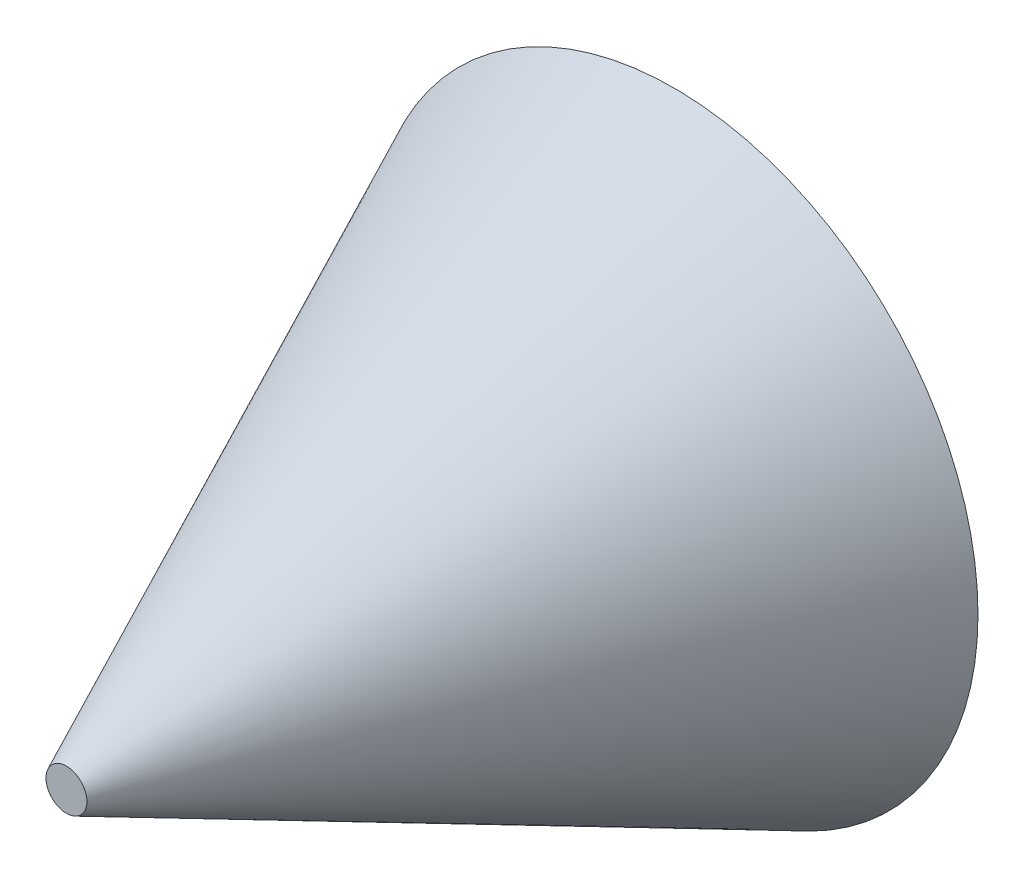
SolidWorks part; units mm, degrees
ref_plane "Front Plane" through (0, 0, 0) normal (0, 0, 1) x (1, 0, 0)
ref_plane "Top Plane" through (0, 0, 0) normal (0, 1, 0) x (1, 0, 0)
ref_plane "Right Plane" through (0, 0, 0) normal (1, 0, 0) x (0, 0, -1)
sketch "Sketch1" plane through (0, 0, 0) normal (0, 0, 1) x (1, 0, 0)
  circle A0 centre (0, 0) radius 12.5
  dimension "D1" = 25
extrude "Boss-Extrude1" add sketch "Sketch1" along normal blind 25 draft 25
